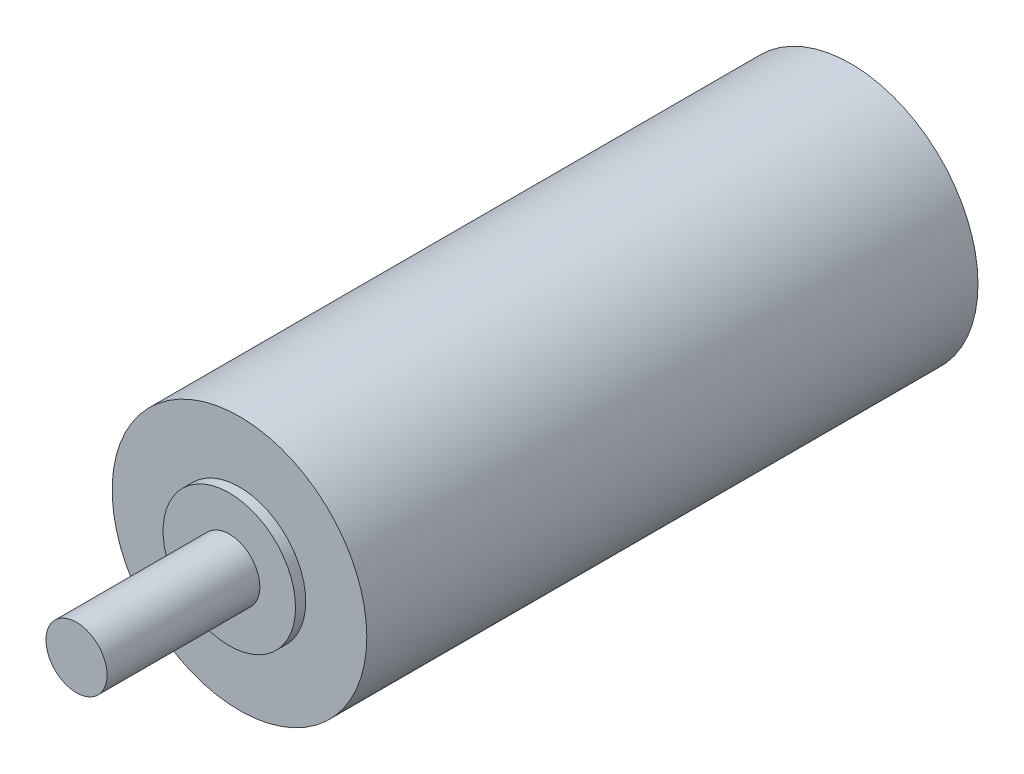
SolidWorks part; units mm, degrees
ref_plane "Plano frontal" through (0, 0, 0) normal (0, 0, 1) x (1, 0, 0)
ref_plane "Plano superior" through (0, 0, 0) normal (0, 1, 0) x (1, 0, 0)
ref_plane "Plano direito" through (0, 0, 0) normal (1, 0, 0) x (0, 0, -1)
sketch "Esboço1" plane through (0, 0, 0) normal (0, 0, 1) x (1, 0, 0)
  circle A0 centre (0, 0) radius 12.5
  dimension "D1" = 25
extrude "Ressalto-extrusão1" add sketch "Esboço1" along normal blind 60
sketch "Esboço2" plane through (0, 0, 60) normal (0, 0, 1) x (1, 0, 0)
  circle A0 centre (0, 0) radius 6.5
  dimension "D1" = 13
extrude "Ressalto-extrusão2" add sketch "Esboço2" along normal blind 1
sketch "Esboço3" plane through (0, 0, 61) normal (0, 0, 1) x (1, 0, 0)
  circle A0 centre (0, 0) radius 3
  dimension "D1" = 6
extrude "Ressalto-extrusão3" add sketch "Esboço3" along normal blind 15
